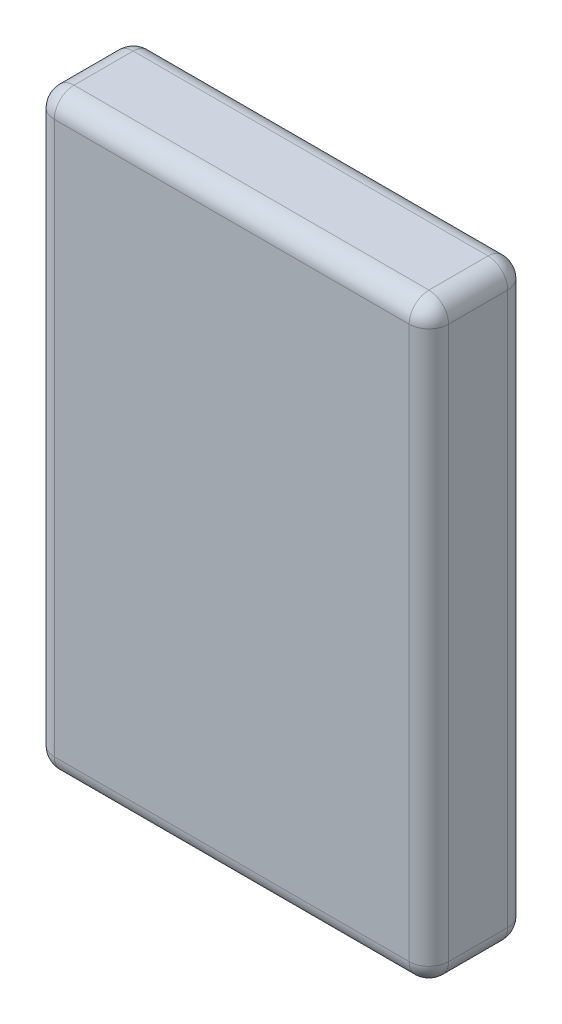
SolidWorks part; units mm, degrees
ref_plane "Front" through (0, 0, 0) normal (0, 0, 1) x (1, 0, 0)
ref_plane "Top" through (0, 0, 0) normal (0, 1, 0) x (1, 0, 0)
ref_plane "Right" through (0, 0, 0) normal (1, 0, 0) x (0, 0, -1)
sketch "Эскиз1" plane through (0, 0, 0) normal (0, 0, 1) x (1, 0, 0)
  line L1 (-2, -3) -> (2, -3)
  line L2 (-2, -3) -> (-2, 3)
  line L3 (-2, 3) -> (2, 3)
  line L4 (2, -3) -> (2, 3)
  line L5 (-2, -3) -> (2, 3) construction
  line L6 (-2, 3) -> (2, -3) construction
  point P0 (0, 0)
  dimension "D1" = 6
  dimension "D2" = 4
extrude "Бобышка-Вытянуть1" add sketch "Эскиз1" along normal blind 1
fillet "Скругление1" radius 0.2 12 edges at (0, 3, 0) (-2, 0, 0) (0, -3, 0) (2, 0, 0) (0, -3, 1) (-2, 0, 1) (0, 3, 1) (2, 0, 1) (-2, 3, 0.5) (2, 3, 0.5) (2, -3, 0.5) (-2, -3, 0.5)
